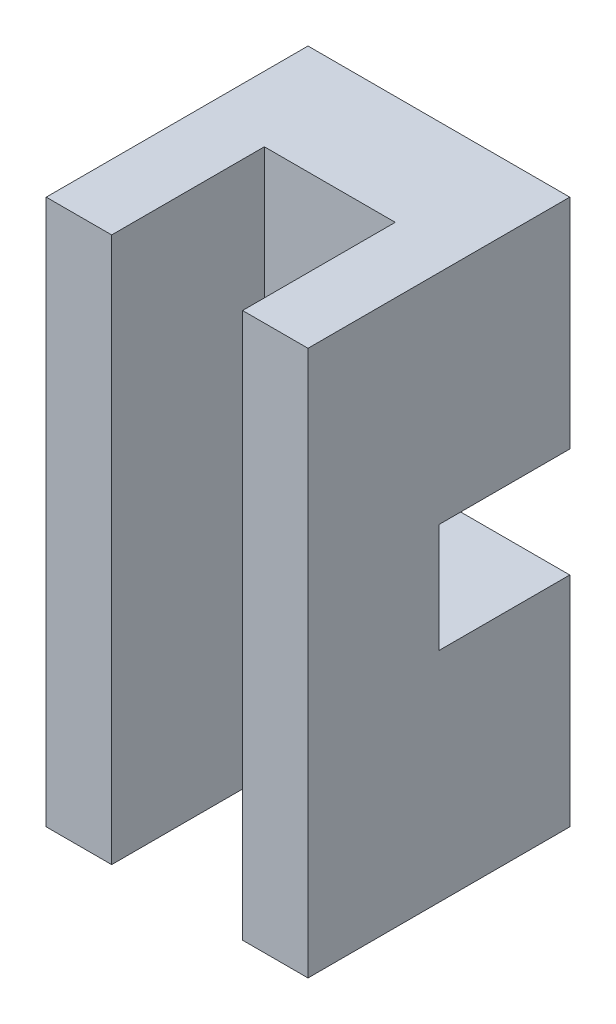
SolidWorks part; units mm, degrees
ref_plane "Front Plane" through (0, 0, 0) normal (1, 0, 0) x (0, 1, 0)
ref_plane "Top Plane" through (0, 0, 0) normal (0, 0, 1) x (0, 1, 0)
ref_plane "Right Plane" through (0, 0, 0) normal (0, 1, 0) x (-1, 0, 0)
sketch "Sketch1" plane through (0, 0, 0) normal (1, 0, 0) x (0, 1, 0)
  line L0 (0, 0) -> (0, 17893.0328) construction
  line L1 (0, 0) -> (17893.0328, 0) construction
  line L2 (-62.5, 30) -> (-62.5, -30)
  line L3 (-62.5, -30) -> (-12.5, -30)
  line L4 (-12.5, -30) -> (-12.5, 0)
  line L5 (-12.5, 0) -> (12.5, 0)
  line L6 (12.5, 0) -> (12.5, -30)
  line L7 (12.5, -30) -> (62.5, -30)
  line L8 (62.5, -30) -> (62.5, 30)
  line L9 (62.5, 30) -> (-62.5, 30)
  point P13 (0, 0)
  dimension "D1" = 25
  dimension "D2" = 50
  dimension "D3" = 60
  dimension "D4" = 30
extrude "Boss-Extrude1" add sketch "Sketch1" along normal mid plane 60
sketch "Sketch2" plane through (0, 62.5, 0) normal (0, 1, 0) x (-1, 0, 0)
  line L0 (-15, 30) -> (-15, -5)
  line L1 (-30, 30) -> (30, 30) construction
  line L2 (-15, -5) -> (15, -5)
  line L3 (15, -5) -> (15, 30)
  line L4 (15, 30) -> (-15, 30)
  line L5 (0, 0) -> (0, -14.9855) construction
  point P9 (0, 0)
  point P10 (0, -5)
  dimension "D1" = 30
  dimension "D2" = 35
extrude "Cut-Extrude1" cut sketch "Sketch2" against normal through all
sketch "Sketch3" plane through (0, 0, -5) normal (0, 0, 1) x (1, 0, 0)
  line L0 (0, 0) -> (45.4346, 0) construction
  circle A0 centre (0, -37.5) radius 5
  circle A1 centre (0, 37.5) radius 5
  point P7 (0, 0)
  dimension "D1" = 10
  dimension "D2" = 75
extrude "Cut-Extrude2" cut sketch "Sketch3" against normal through all
